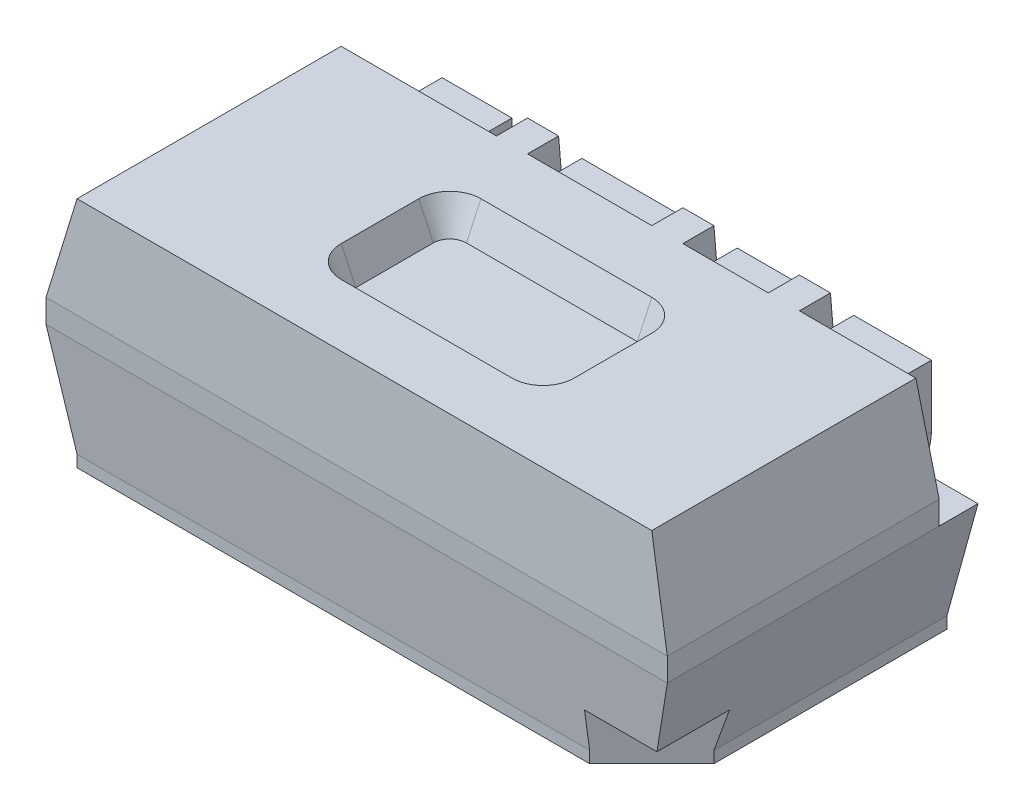
SolidWorks part; units mm, degrees
ref_plane "Front" through (0, 0, 0) normal (0, 0, 1) x (1, 0, 0)
ref_plane "Top" through (0, 0, 0) normal (0, 1, 0) x (1, 0, 0)
ref_plane "Right" through (0, 0, 0) normal (1, 0, 0) x (0, 0, -1)
sketch "Эскиз1" plane through (0, 0, 0) normal (1, 0, 0) x (0, -1, 0)
  line L0 (-0.15, -2) -> (0, -2)
  line L1 (0, -2) -> (0.675, -1.95)
  line L3 (0.675, -0.05) -> (0, 0)
  line L4 (0, 0) -> (-0.15, 0)
  line L5 (-0.15, 0) -> (-0.75, -0.05)
  line L6 (-0.75, -0.05) -> (-0.75, -1.95)
  line L7 (-0.75, -1.95) -> (-0.15, -2)
  line L8 (0, -2) -> (0, 0) construction
  line L9 (-0.75, -1) -> (0.75, -1) construction
  line L10 (0.675, -1.95) -> (0.75, -1.95)
  line L11 (0.75, -1.95) -> (0.75, -0.05)
  line L12 (0.75, -0.05) -> (0.675, -0.05)
  line L13 (0.675, -1.95) -> (-0.75, -1.95) construction
  point P2 (0.75, -1)
  point P10 (0, -1)
  point P11 (0, -1)
  dimension "D1" = 1.5
  dimension "D2" = 0.15
  dimension "D3" = 0.075
  dimension "D4" = 1.9
  dimension "D5" = 2
extrude "Бобышка-Вытянуть1" add sketch "Эскиз1" along normal mid plane 4
sketch "Эскиз2" plane through (0, 0, 0) normal (0, 0, 1) x (1, 0, 0)
  line L0 (-2, 0) -> (2, 0) construction
  line L1 (2, 0) -> (1.85, -0.675)
  line L2 (1.85, -0.675) -> (-1.85, -0.675) construction
  line L3 (-1.85, -0.675) -> (-2, 0)
  line L4 (-2, 0) -> (-2, 0.15)
  line L5 (-2, 0.15) -> (-1.85, 0.75)
  line L6 (-1.85, 0.75) -> (1.85, 0.75)
  line L7 (1.85, 0.75) -> (2, 0.15)
  line L8 (2, 0.15) -> (2, 0)
  line L9 (0, 0.75) -> (0, -0.675) construction
  line L12 (2, -0.675) -> (-2, -0.675) construction
  line L13 (2, 0.75) -> (-2, 0.75) construction
  line L14 (2, 0) -> (-2, 0) construction
  line L15 (2, 0) -> (2, 0.15) construction
  line L16 (1.85, 0.75) -> (1.85, -0.675) construction
  line L17 (1.85, -0.675) -> (1.85, -0.75)
  line L18 (1.85, -0.75) -> (-1.85, -0.75)
  line L19 (-1.85, -0.75) -> (-1.85, -0.675)
  line L20 (2, -0.75) -> (-2, -0.75) construction
  dimension "D1" = 0.15
extrude "Вырез-Вытянуть1" cut sketch "Эскиз2" along normal through all flip side to cut
sketch "Эскиз4" plane through (0, -0.75, 0) normal (0, -1, 0) x (1, 0, 0)
  line L0 (2, 2) -> (2, 1.4)
  line L1 (2, 1.4) -> (1.4, 2)
  line L2 (1.4, 2) -> (2, 2)
  line L3 (2, 2) -> (2, 0) construction
  line L4 (2, 2) -> (-2, 2) construction
  dimension "D1" = 0.6
extrude "Вырез-Вытянуть2" cut sketch "Эскиз4" against normal blind 0.3
sketch "Эскиз7" plane through (0, 0, 0) normal (1, 0, 0) x (0, 0, -1)
  line L0 (0, 0.65) -> (0, 0.25)
  line L1 (-0.25, 0) -> (-0.4728, 0) construction
  line L2 (-2, 0) -> (0, 0) construction
  line L3 (-0.25, 0) -> (-0.25, 0.75) construction
  arc A0 (0, 0.25) -> (-0.25, 0) centre (-0.25, 0.25) cw
  dimension "D1" = 0.65
  dimension "D2" = 0.25
ref_plane "Плоскость1" through (0, 0.65, 0) normal (0, 1, 0) x (1, 0, 0)
sketch "Эскиз6" plane through (0, 0.65, 0) normal (0, 1, 0) x (1, 0, 0)
  line L2 (-0.55, 0) -> (-0.55, -0.15)
  line L3 (-0.55, -0.15) -> (0.05, -0.15)
  line L4 (0.05, -0.15) -> (0.05, 0)
  line L5 (-1, 0) -> (-1.45, 0)
  line L7 (-1.45, 0) -> (-1.45, -0.15)
  line L8 (-1.45, -0.15) -> (-1, -0.15)
  line L9 (-1, -0.15) -> (-1, 0)
  line L10 (0.45, 0) -> (0.8, 0)
  line L12 (0.8, 0) -> (0.8, -0.15)
  line L14 (0.45, -0.15) -> (0.45, 0)
  line L15 (1.2, 0) -> (1.7, 0)
  line L17 (1.7, 0) -> (1.7, -0.15)
  line L19 (1.2, -0.15) -> (1.2, 0)
  line L20 (0.45, -0.15) -> (0.8, -0.15)
  line L21 (1.7, -0.15) -> (1.2, -0.15)
  line L22 (-0.55, -0.15) -> (-1, -0.15) construction
  line L23 (0.05, -0.15) -> (0.45, -0.15) construction
  line L24 (0.8, -0.15) -> (1.2, -0.15) construction
  line L25 (-0.55, 0) -> (0.05, 0)
  line L26 (2, -2) -> (2, 0) construction
  line L27 (-2, -2) -> (-2, 0) construction
  dimension "D1" = 0.15
  dimension "D2" = 0.5
  dimension "D3" = 0.35
  dimension "D4" = 0.6
  dimension "D5" = 0.45
  dimension "D6" = 0.45
  dimension "D7" = 0.4
  dimension "D8" = 0.4
  dimension "D9" = 0.3
  dimension "D10" = 0.55
sweep "По траектории3" add profiles "Эскиз6" path "Эскиз7"
sketch "Эскиз5" plane through (0, 0.75, 0) normal (0, 1, 0) x (1, 0, 0)
  line L8 (0.15, 0) -> (-0.65, 0)
  line L9 (-0.65, 0) -> (-0.65, -0.25)
  line L10 (-0.65, -0.25) -> (0.15, -0.25)
  line L11 (0.15, -0.25) -> (0.15, 0)
  line L12 (-0.85, 0) -> (-2, 0)
  line L13 (-2, 0) -> (-2, -0.25)
  line L14 (-2, -0.25) -> (-0.85, -0.25)
  line L15 (-0.85, -0.25) -> (-0.85, 0)
  line L16 (0.35, 0) -> (0.9, 0)
  line L17 (0.9, 0) -> (0.9, -0.25)
  line L18 (0.9, -0.25) -> (0.35, -0.25)
  line L19 (0.35, -0.25) -> (0.35, 0)
  line L24 (1.1, -0.25) -> (2, -0.25)
  line L25 (2, -0.25) -> (2, 0)
  line L26 (2, 0) -> (1.1, 0)
  line L27 (1.1, 0) -> (1.1, -0.25)
  line L28 (-2, -2) -> (-2, 0) construction
  line L29 (2, -2) -> (2, 0) construction
  line L30 (1.1, -0.25) -> (0.9, -0.25) construction
  line L31 (0.35, -0.25) -> (0.15, -0.25) construction
  line L32 (-0.65, -0.25) -> (-0.85, -0.25) construction
  line L33 (0.8, 0) -> (0.45, 0) construction
  line L34 (0.05, 0) -> (-0.55, 0) construction
  line L35 (0.05, -0.0417) -> (0.45, -0.0417) construction
  line L36 (0.25, -0.0417) -> (0.25, -0.25) construction
  line L37 (0.45, 0) -> (0.45, -0.15) construction
  line L38 (0.05, -0.15) -> (0.05, 0) construction
  point P8 (-0.25, 0)
  point P27 (-0.25, 0)
  point P28 (0.625, 0)
  point P32 (0.625, 0)
  dimension "D1" = 0.2
extrude "Вырез-Вытянуть4" cut sketch "Эскиз5" against normal up to surface (0.75 mm away) up to plane "Top"
sketch "Эскиз9" plane through (0, 0.75, 0) normal (0, 1, 0) x (1, 0, 0)
  line L0 (0, 0) -> (0, -1.1) construction
  line L1 (-0.55, -0.65) -> (0.55, -0.65)
  line L2 (-0.75, -0.85) -> (-0.75, -1.35)
  line L3 (-0.55, -1.55) -> (0.55, -1.55)
  line L4 (0.75, -0.85) -> (0.75, -1.35)
  line L5 (-0.75, -0.65) -> (0.75, -1.55) construction
  line L6 (-0.75, -1.55) -> (0.75, -0.65) construction
  line L7 (0.75, -1.55) -> (1.85, -1.55) construction
  line L8 (1.85, -1.95) -> (1.85, -0.25) construction
  line L9 (-0.75, -1.55) -> (-1.85, -1.55) construction
  line L10 (-0.75, -1.55) -> (-0.75, -1.95) construction
  line L11 (1.85, -1.95) -> (-1.85, -1.95) construction
  line L12 (-0.75, -0.65) -> (-0.75, -0.25) construction
  line L14 (-0.65, -0.25) -> (0.15, -0.25) construction
  arc A0 (0.75, -1.35) -> (0.55, -1.55) centre (0.55, -1.35) cw
  arc A1 (-0.55, -1.55) -> (-0.75, -1.35) centre (-0.55, -1.35) cw
  arc A2 (-0.75, -0.85) -> (-0.55, -0.65) centre (-0.55, -0.85) cw
  arc A3 (0.55, -0.65) -> (0.75, -0.85) centre (0.55, -0.85) cw
  point P0 (0, -1.1)
  dimension "D2" = 0.2
  dimension "D1" = 0.4
extrude "Вырез-Вытянуть5" cut sketch "Эскиз9" against normal blind 0.2 draft 25
sketch "Эскиз10" plane through (0, -0.75, 0) normal (0, -1, 0) x (-1, 0, 0)
  line L0 (1.1, -1.8) -> (-1.1, -1.8)
  line L1 (-1.1, -1.8) -> (-1.45, -1.45)
  line L2 (-1.45, -1.45) -> (-1.45, -0.65)
  line L3 (-1.45, -0.65) -> (-1.1, -0.3)
  line L4 (-1.1, -0.3) -> (1.1, -0.3)
  line L5 (1.1, -0.3) -> (1.45, -0.65)
  line L6 (1.45, -0.65) -> (1.45, -1.45)
  line L7 (1.45, -1.45) -> (1.1, -1.8)
  line L8 (-1.4333, -1.9667) -> (-1.9, -1.5) construction
  line L9 (-1.85, -0.05) -> (1.85, -0.05) construction
  line L10 (-1.85, -1.55) -> (-1.85, -0.05) construction
  line L11 (-1.45, -1.95) -> (1.85, -1.95) construction
  line L12 (1.85, -1.95) -> (1.85, -0.05) construction
  dimension "D1" = 0.25
  dimension "D2" = 0.4
  dimension "D3" = 0.15
  dimension "D4" = 0.4
  dimension "D5" = 0.35
extrude "Вырез-Вытянуть6" cut sketch "Эскиз10" against normal blind 0.01
